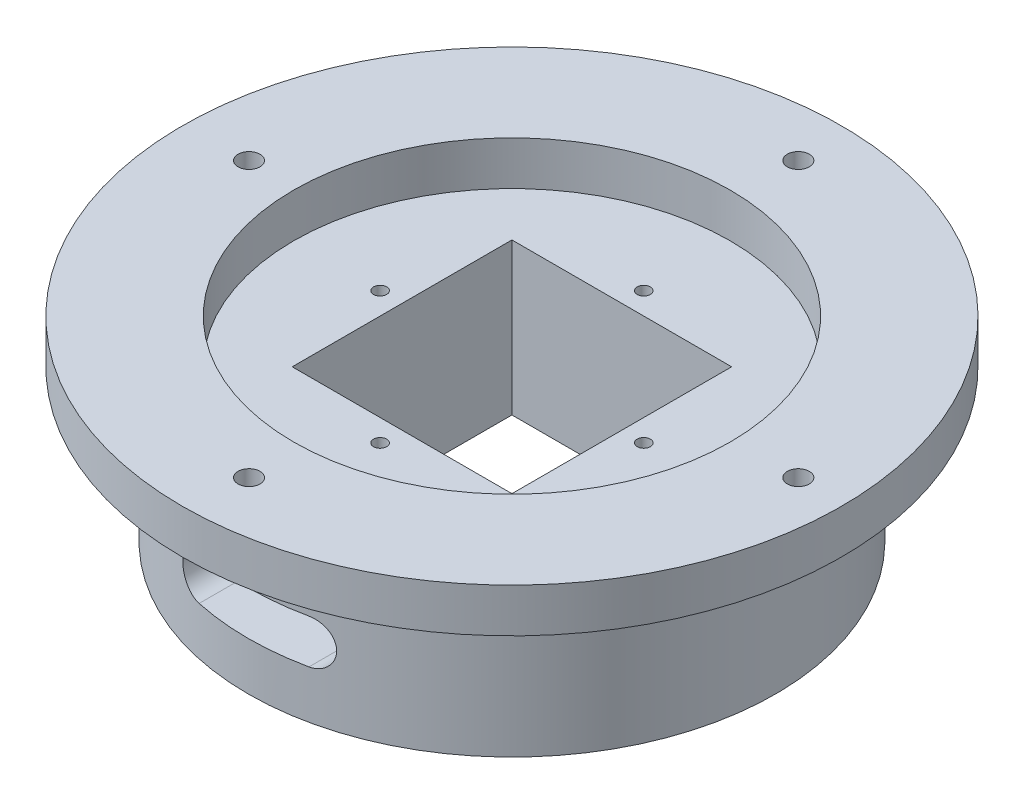
SolidWorks part; units mm, degrees
ref_plane "前视基准面" through (0, 0, 0) normal (0, 0, 1) x (1, 0, 0)
ref_plane "上视基准面" through (0, 0, 0) normal (0, 1, 0) x (1, 0, 0)
ref_plane "右视基准面" through (0, 0, 0) normal (1, 0, 0) x (0, 0, -1)
sketch "草图1" plane through (0, 0, 0) normal (0, 1, 0) x (1, 0, 0)
  line L1 (-90.6561, 58.526) -> (29.3439, 58.526)
  line L2 (-90.6561, 58.526) -> (-90.6561, -61.474)
  line L3 (-90.6561, -61.474) -> (29.3439, -61.474)
  line L4 (29.3439, 58.526) -> (29.3439, -61.474)
  line L5 (-30.6561, -61.474) -> (-30.6561, 58.526) construction
  line L6 (-90.6561, -1.474) -> (29.3439, -1.474) construction
  line L7 (-80.6561, 48.526) -> (19.3439, 48.526)
  line L8 (-80.6561, 48.526) -> (-80.6561, -51.474)
  line L9 (-80.6561, -51.474) -> (19.3439, -51.474)
  line L10 (19.3439, 48.526) -> (19.3439, -51.474)
  line L11 (-30.6561, -51.474) -> (-30.6561, 48.526) construction
  line L12 (-80.6561, -1.474) -> (19.3439, -1.474) construction
  circle A0 centre (-30.6561, -1.474) radius 120
  circle A1 centre (-90.6561, -1.474) radius 3
  circle A2 centre (29.3439, -1.474) radius 3
  circle A3 centre (-30.6561, -61.474) radius 3
  circle A4 centre (-30.6561, 58.526) radius 3
  point P15 (-35.6561, -6.474)
  point P18 (-35.6561, -6.474)
  dimension "D1" = 120
  dimension "D3" = 240
  dimension "D5" = 100
  dimension "D2" = 120
  dimension "D6" = 100
extrude "凸台-拉伸3" add sketch "草图1" along normal blind 69 contours A0 A4 L1 L4 A2 L3 A3 L2 A1 | A4 L1 L2 A1 L3 A3 L4 A2 L7 L10 L9 L8
sketch "草图8" plane through (0, 69, 0) normal (0, 1, 0) x (1, 0, 0)
  circle A0 centre (-30.6561, -1.474) radius 150
  circle A1 centre (-30.6561, -1.474) radius 99.3373
extrude "凸台-拉伸6" add sketch "草图8" along normal blind 20
sketch "草图9" plane through (0, 89, 0) normal (0, 1, 0) x (1, 0, 0)
  circle A0 centre (-26.7877, 0) radius 125
  circle A1 centre (-26.7877, 125) radius 5
  circle A2 centre (98.2123, 0) radius 5
  circle A3 centre (-26.7877, -125) radius 5
  circle A4 centre (-151.7877, 0) radius 5
  point P13 (-26.7877, 0)
  dimension "D1" = 4
extrude "切除-拉伸11" cut sketch "草图9" against normal blind 10 contours A4 | A1 | A2 | A3
sketch "草图10" plane through (0, 0, 51.474) normal (0, 0, -1) x (-1, 0, 0)
  line L1 (55.6561, 31.8994) -> (5.6562, 31.8994) construction
  line L7 (55.6561, 21.8994) -> (5.6562, 21.8994)
  line L8 (55.6561, 41.8994) -> (5.6562, 41.8994)
  line L9 (80.6561, 69) -> (80.6561, 0) construction
  line L10 (-19.3439, 69) -> (-19.3439, 0) construction
  line L11 (80.6561, 0) -> (-19.3439, 0) construction
  arc A2 (55.6561, 21.8994) -> (55.6561, 41.8994) centre (55.6561, 31.8994) ccw
  arc A3 (5.6562, 41.8994) -> (5.6562, 21.8994) centre (5.6562, 31.8994) ccw
  point P2 (30.6561, 31.8994)
  dimension "D1" = 25
  dimension "D2" = 25.0001
  dimension "D3" = 0
extrude "切除-拉伸12" cut sketch "草图10" against normal blind 76
